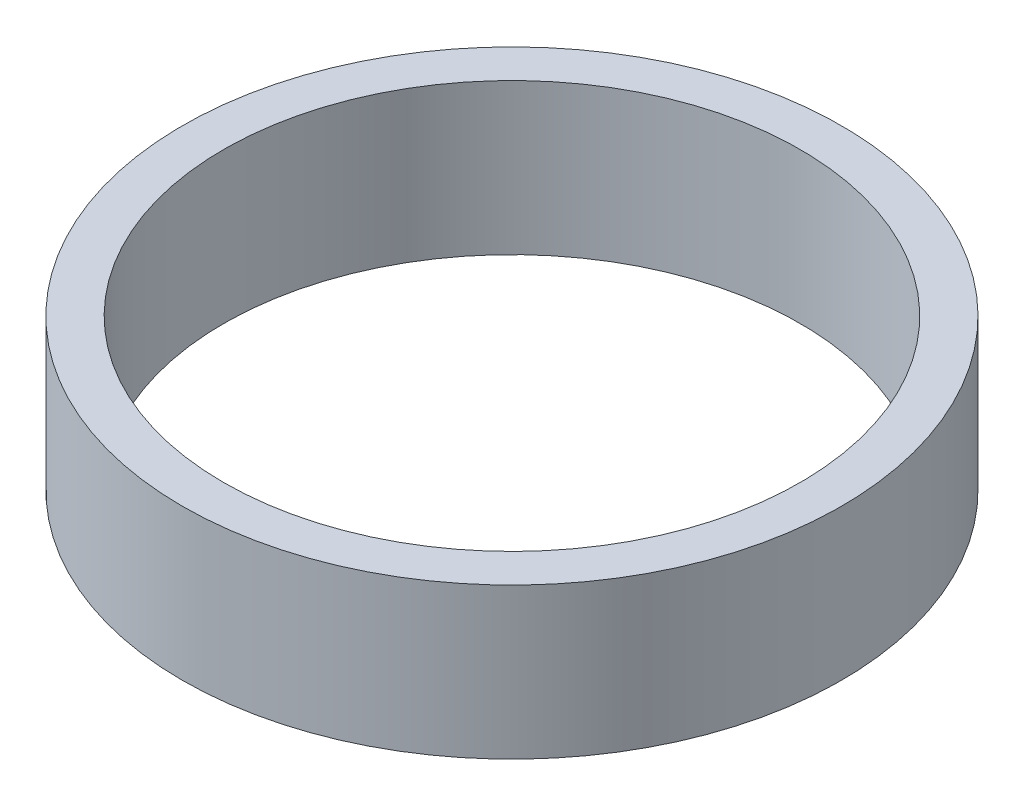
SolidWorks part; units mm, degrees
material "AISI 304"
ref_plane "Спереди" through (0, 0, 0) normal (0, 0, 1) x (1, 0, 0)
ref_plane "Сверху" through (0, 0, 0) normal (0, 1, 0) x (1, 0, 0)
ref_plane "Справа" through (0, 0, 0) normal (1, 0, 0) x (0, 0, -1)
sketch "Эскиз1" plane through (0, 0, 0) normal (0, 1, 0) x (1, 0, 0)
  circle A0 centre (0, 0) radius 40
  circle A1 centre (0, 0) radius 35
  dimension "D1" = 80
  dimension "D2" = 70
extrude "Бобышка-Вытянуть1" add sketch "Эскиз1" along normal blind 18.3
